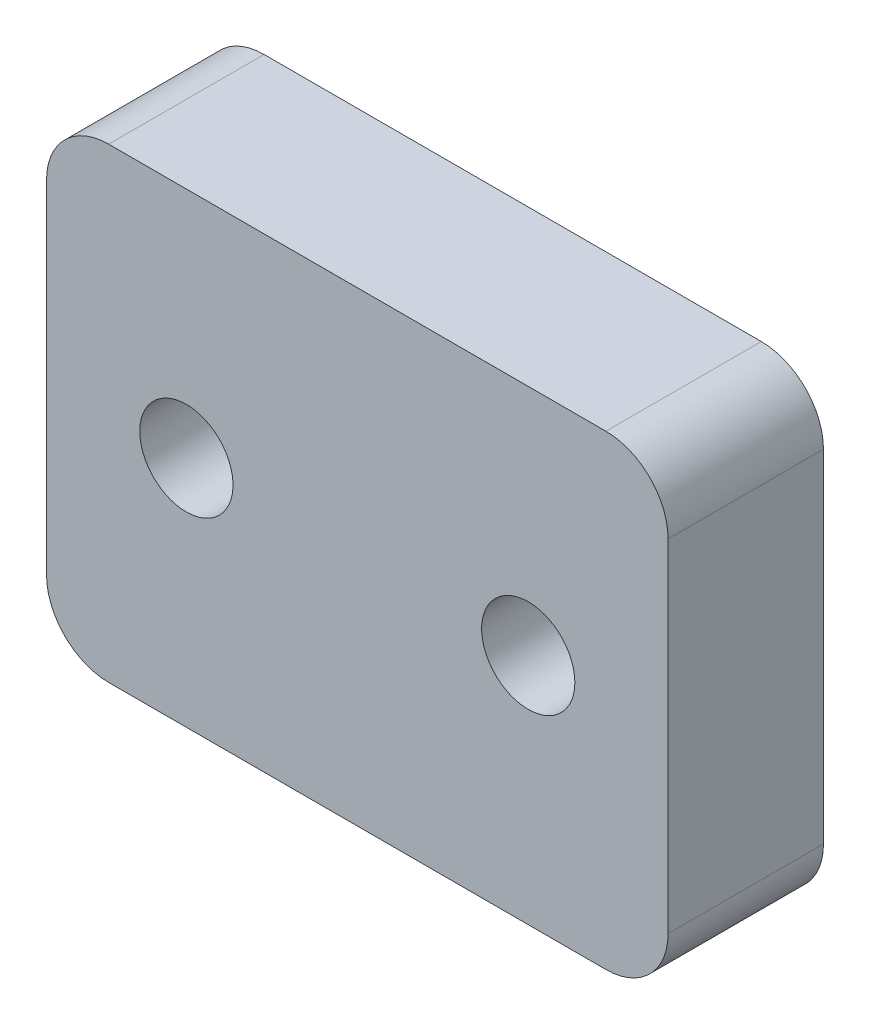
SolidWorks part; units mm, degrees
ref_plane "前视基准面" through (0, 0, 0) normal (0, 0, 1) x (1, 0, 0)
ref_plane "上视基准面" through (0, 0, 0) normal (0, 1, 0) x (1, 0, 0)
ref_plane "右视基准面" through (0, 0, 0) normal (1, 0, 0) x (0, 0, -1)
sketch "草图1" plane through (0, 0, 0) normal (0, 0, 1) x (1, 0, 0)
  line L1 (10, -7.5) -> (-10, -7.5)
  line L2 (10, -7.5) -> (10, 7.5)
  line L3 (10, 7.5) -> (-10, 7.5)
  line L4 (-10, -7.5) -> (-10, 7.5)
  line L5 (10, -7.5) -> (-10, 7.5) construction
  line L6 (10, 7.5) -> (-10, -7.5) construction
  point P0 (0, 0)
  dimension "D1" = 20
  dimension "D2" = 15
extrude "凸台-拉伸1" add sketch "草图1" along normal blind 5
sketch "草图3" plane through (0, 0, 5) normal (0, 0, 1) x (1, 0, 0)
  line L0 (0, 0) -> (5.5, 0) construction
  line L1 (0, -55) -> (0, 55) construction
  circle A0 centre (5.5, 0) radius 1.5
  circle A1 centre (-5.5, 0) radius 1.5
  dimension "D1" = 5.5
  dimension "D2" = 3
extrude "切除-拉伸2" cut sketch "草图3" against normal through all
fillet "圆角1" radius 2 4 edges at (10, -7.5, 2.5) (10, 7.5, 2.5) (-10, 7.5, 2.5) (-10, -7.5, 2.5)
